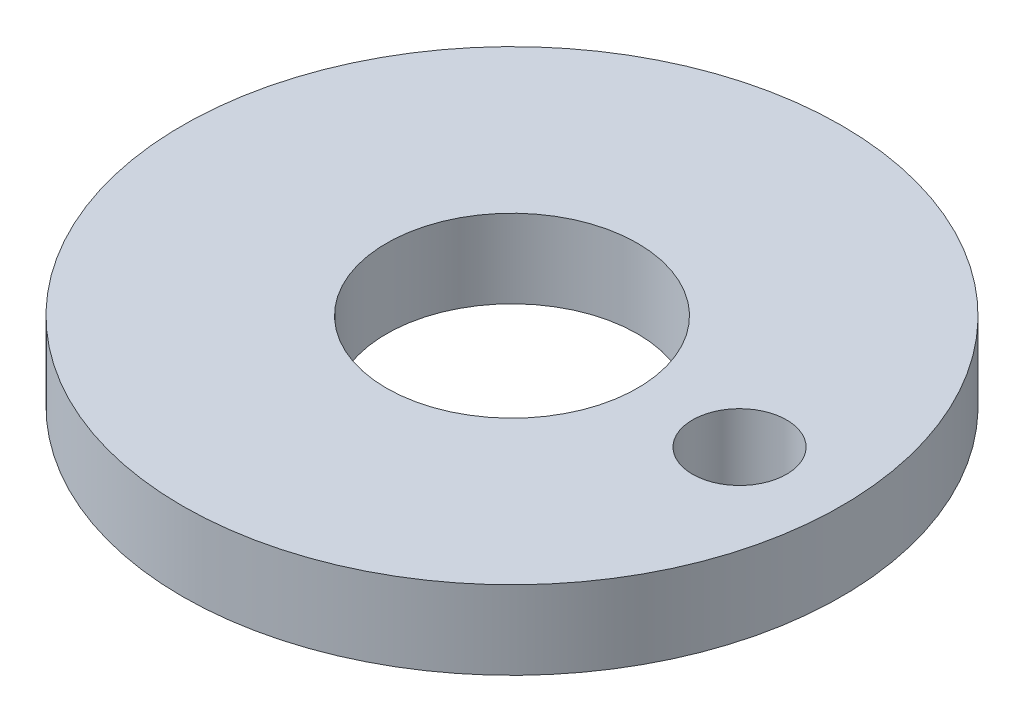
SolidWorks part; units mm, degrees
ref_plane "Front Plane" through (0, 0, 0) normal (0, 0, 1) x (1, 0, 0)
ref_plane "Top Plane" through (0, 0, 0) normal (0, 1, 0) x (1, 0, 0)
ref_plane "Right Plane" through (0, 0, 0) normal (1, 0, 0) x (0, 0, -1)
sketch "Sketch1" plane through (0, 0, 0) normal (0, 1, 0) x (1, 0, 0)
  circle A0 centre (0, 0) radius 10.5
  dimension "D1" = 21
extrude "Boss-Extrude1" add sketch "Sketch1" along normal blind 2.5
sketch "Sketch2" plane through (0, 2.5, 0) normal (0, 1, 0) x (1, 0, 0)
  circle A0 centre (0, 0) radius 4
  circle A1 centre (7.25, 0) radius 1.5
  point P5 (0, 0)
  dimension "D1" = 8
  dimension "D2" = 7.25
  dimension "D3" = 3
extrude "Cut-Extrude1" cut sketch "Sketch2" against normal blind 10
